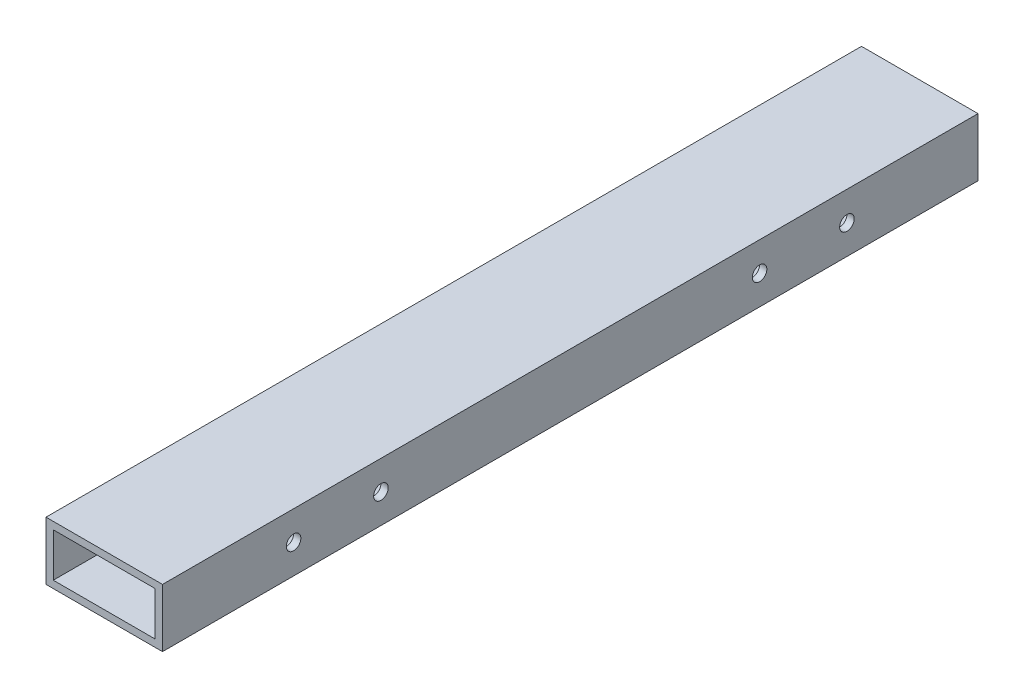
SolidWorks part; units mm, degrees
ref_plane "Front Plane" through (0, 0, 0) normal (0, 0, 1) x (1, 0, 0)
ref_plane "Top Plane" through (0, 0, 0) normal (0, 1, 0) x (1, 0, 0)
ref_plane "Right Plane" through (0, 0, 0) normal (1, 0, 0) x (0, 0, -1)
sketch "Sketch1" plane through (0, 0, 0) normal (0, 0, 1) x (1, 0, 0)
  line L0 (3.175, 22.225) -> (47.625, 22.225)
  line L1 (0, 0) -> (50.8, 0)
  line L2 (0, 0) -> (0, 25.4)
  line L3 (0, 25.4) -> (50.8, 25.4)
  line L4 (50.8, 0) -> (50.8, 25.4)
  line L5 (47.625, 3.175) -> (47.625, 22.225)
  line L6 (3.175, 3.175) -> (47.625, 3.175)
  line L7 (3.175, 3.175) -> (3.175, 22.225)
  dimension "D1" = 25.4
  dimension "D2" = 50.8
  dimension "D3" = 3.175
extrude "Boss-Extrude1" add sketch "Sketch1" along normal blind 355.6
sketch "Sketch2" plane through (50.8, 0, 0) normal (1, 0, 0) x (0, 0, -1)
  line L0 (-177.8, 25.4) -> (-177.8, 12.7) construction
  line L1 (-355.6, 25.4) -> (0, 25.4) construction
  line L2 (-177.8, 12.7) -> (-260.35, 12.7) construction
  line L3 (-260.35, 12.7) -> (-298.45, 12.7) construction
  circle A0 centre (-260.35, 12.7) radius 3.175
  circle A1 centre (-298.45, 12.7) radius 3.175
  circle A2 centre (-57.15, 12.7) radius 3.175
  circle A3 centre (-95.25, 12.7) radius 3.175
  dimension "D4" = 6.35
  dimension "D1" = 12.7
  dimension "D2" = 38.1
  dimension "D3" = 82.55
extrude "Cut-Extrude1" cut sketch "Sketch2" against normal through all both
